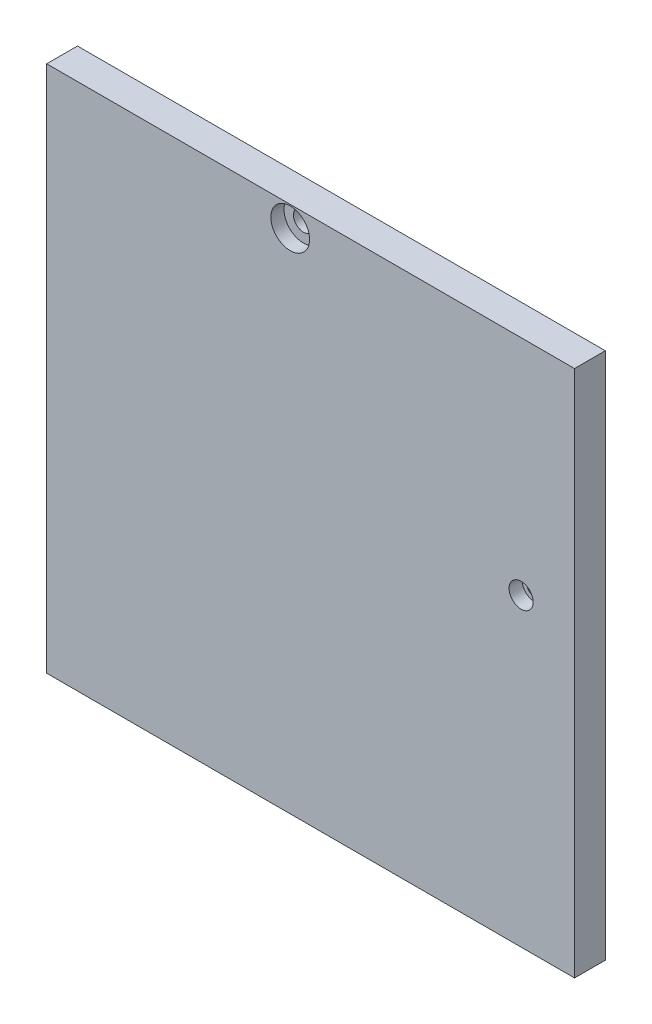
SolidWorks part; units mm, degrees
ref_plane "前视基准面" through (0, 0, 0) normal (0, 0, 1) x (1, 0, 0)
ref_plane "上视基准面" through (0, 0, 0) normal (0, 1, 0) x (1, 0, 0)
ref_plane "右视基准面" through (0, 0, 0) normal (1, 0, 0) x (0, 0, -1)
other "Configuration Table"
sketch "草图5" plane through (0, 0, 0) normal (0, 0, 1) x (1, 0, 0)
  line L1 (-55.3616, 77.4232) -> (64.6384, 77.4232)
  line L2 (-55.3616, 77.4232) -> (-55.3616, -42.5768)
  line L3 (-55.3616, -42.5768) -> (64.6384, -42.5768)
  line L4 (64.6384, 77.4232) -> (64.6384, -42.5768)
extrude "凸台-拉伸2" add sketch "草图5" along normal blind 7
sketch "草图6" plane through (0, 0, 7) normal (0, 0, 1) x (1, 0, 0)
  circle A0 centre (0, 72.7103) radius 4.4069
  circle A1 centre (0, 72.7103) radius 2.2617
extrude "切除-拉伸1" cut sketch "草图6" against normal blind 7 contours A1
sketch "草图9" plane through (0, 0, 7) normal (0, 0, 1) x (1, 0, 0)
  circle A0 centre (0, 72.7103) radius 4.4069
extrude "切除-拉伸2" cut sketch "草图9" against normal blind 3
sketch "草图10" plane through (0, 0, 7) normal (0, 0, 1) x (1, 0, 0)
  line L0 (0, 72.7103) -> (0, 26.7103)
  line L1 (0, 26.7103) -> (52.5, 26.7103)
  circle A0 centre (52.5, 26.7103) radius 1.7558
extrude "切除-拉伸3" cut sketch "草图10" against normal blind 7 contours A0
sketch "草图11" plane through (0, 0, 7) normal (0, 0, 1) x (1, 0, 0)
  circle A0 centre (52.5, 26.7103) radius 2.7449
extrude "切除-拉伸4" cut sketch "草图11" against normal blind 3
sketch "草图12" plane through (0, 0, 7) normal (0, 0, 1) x (1, 0, 0)
  line L0 (52.5, 26.7103) -> (-52.5, 26.7103)
  line L2 (-55.3616, -42.5768) -> (-58.3616, -42.5768)
  line L3 (-58.3616, -42.5768) -> (-58.3616, 77.4232)
  line L4 (-58.3616, 77.4232) -> (-55.3616, 77.4232)
  point P3 (0, 0)
  point P8 (0, 0)
